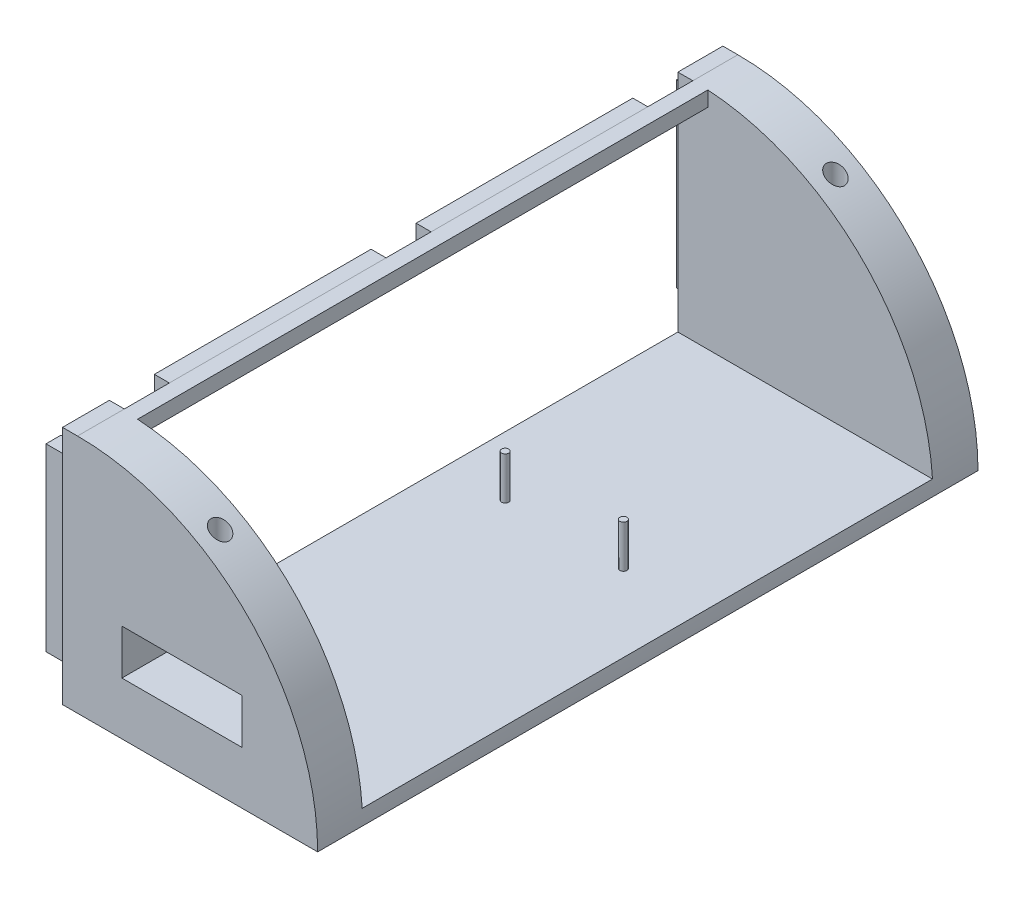
SolidWorks part; units mm, degrees
ref_plane "Front Plane" through (0, 0, 0) normal (0, 0, 1) x (1, 0, 0)
ref_plane "Top Plane" through (0, 0, 0) normal (0, 1, 0) x (1, 0, 0)
ref_plane "Right Plane" through (0, 0, 0) normal (1, 0, 0) x (0, 0, -1)
sketch "Sketch1" plane through (0, 0, 0) normal (0, 0, 1) x (1, 0, 0)
  line L0 (0, 0) -> (0, 50.8)
  line L1 (0, 0) -> (50.8, 0)
  arc A0 (0, 50.8) -> (50.8, 0) centre (0, 0) cw
  dimension "D1" = 50.8
  dimension "D2" = 50.8
extrude "Boss-Extrude1" add sketch "Sketch1" along normal blind 139.7
shell "Shell1" thickness 3.175
sketch "Sketch3" plane through (0, 0, 139.7) normal (0, 0, 1) x (1, 0, 0)
  line L0 (0, 50.8) -> (0, 0)
  line L1 (0, 0) -> (50.8, 0)
  arc A0 (0, 50.8) -> (50.8, 0) centre (0, 0) cw
extrude "Boss-Extrude2" add sketch "Sketch3" against normal blind 9.525
sketch "Sketch4" plane through (0, 0, 0) normal (0, 0, -1) x (-1, 0, 0)
  line L0 (-50.8, 0) -> (0, 0)
  line L1 (0, 0) -> (0, 50.8)
  arc A0 (-50.8, 0) -> (0, 50.8) centre (0, 0) cw
extrude "Boss-Extrude3" add sketch "Sketch4" against normal blind 9.525
sketch "Sketch5" plane through (0, 0, 0) normal (-1, 0, 0) x (0, 0, 1)
  line L1 (9.525, 47.625) -> (130.175, 47.625)
  line L2 (9.525, 47.625) -> (9.525, 3.175)
  line L3 (9.525, 3.175) -> (130.175, 3.175)
  line L4 (130.175, 47.625) -> (130.175, 3.175)
  line L5 (0, 50.8) -> (139.7, 50.8)
  line L6 (0, 50.8) -> (0, 0)
  line L7 (0, 0) -> (139.7, 0)
  line L8 (139.7, 50.8) -> (139.7, 0)
extrude "Boss-Extrude4" add sketch "Sketch5" along normal blind 3.175
sketch "Sketch6" plane through (-3.175, 0, 0) normal (-1, 0, 0) x (0, 0, 1)
  line L0 (0, 50.8) -> (0, 0) construction
  line L1 (1.5875, 6.35) -> (4.7625, 6.35)
  line L2 (1.5875, 6.35) -> (1.5875, 44.45)
  line L3 (1.5875, 44.45) -> (4.7625, 44.45)
  line L4 (4.7625, 6.35) -> (4.7625, 44.45)
  line L5 (1.5875, 6.35) -> (4.7625, 44.45) construction
  line L6 (1.5875, 44.45) -> (4.7625, 6.35) construction
  line L7 (139.7, 50.8) -> (0, 50.8) construction
  line L8 (69.85, 47.625) -> (69.85, 3.175) construction
  line L9 (130.175, 47.625) -> (9.525, 47.625) construction
  line L10 (9.525, 3.175) -> (130.175, 3.175) construction
  line L11 (138.1125, 44.45) -> (134.9375, 44.45)
  line L12 (134.9375, 6.35) -> (134.9375, 44.45)
  line L13 (138.1125, 6.35) -> (134.9375, 6.35)
  line L14 (138.1125, 6.35) -> (138.1125, 44.45)
  point P0 (3.175, 25.4)
  dimension "D1" = 38.1
  dimension "D2" = 3.175
  dimension "D3" = 3.175
  dimension "D4" = 25.4
extrude "Boss-Extrude5" add sketch "Sketch6" along normal blind 5.08
sketch "Sketch7" plane through (0, 50.8, 0) normal (0, 1, 0) x (1, 0, 0)
  line L0 (0, -139.7) -> (0, 0) construction
  line L1 (-3.175, -9.525) -> (0, -9.525)
  line L2 (-3.175, -9.525) -> (-3.175, -19.05)
  line L3 (-3.175, -19.05) -> (0, -19.05)
  line L4 (0, -9.525) -> (0, -19.05)
  line L5 (-3.175, -64.897) -> (-3.175, -74.422)
  line L6 (-3.175, -64.897) -> (0, -64.897)
  line L7 (0, -64.897) -> (0, -74.422)
  line L8 (-3.175, -74.422) -> (0, -74.422)
  line L9 (-3.175, -120.269) -> (-3.175, -129.794)
  line L10 (-3.175, -120.269) -> (0, -120.269)
  line L11 (0, -120.269) -> (0, -129.794)
  line L12 (-3.175, -129.794) -> (0, -129.794)
  dimension "D1" = 9.525
  dimension "D2" = 3
extrude "Cut-Extrude1" cut sketch "Sketch7" against normal up to surface (3.175 mm away) up to face at (-1.5875, 47.625, 69.85)
sketch "Sketch9" plane through (0, 3.175, 0) normal (0, 1, 0) x (1, 0, 0)
  line L0 (50.8, -139.7) -> (50.8, 0) construction
  line L1 (3.175, -9.525) -> (50.8, -9.525)
  line L2 (3.175, -9.525) -> (3.175, -130.175)
  line L3 (3.175, -130.175) -> (50.8, -130.175)
  line L4 (50.8, -9.525) -> (50.8, -130.175)
  line L5 (50.8, 0) -> (0, 0) construction
  line L6 (0, -139.7) -> (50.8, -139.7) construction
  line L7 (-3.175, -120.269) -> (-3.175, -74.422) construction
  dimension "D1" = 9.525
  dimension "D2" = 9.525
  dimension "D3" = 6.35
extrude "Cut-Extrude2" cut sketch "Sketch9" along normal through all
sketch "Sketch8" plane through (0, 3.175, 0) normal (0, 1, 0) x (1, 0, 0)
  circle A0 centre (34.3737, -124.5927) radius 0.75
  circle A1 centre (34.3737, -58.5927) radius 0.75
  circle A2 centre (9.3737, -58.5927) radius 0.75
  circle A3 centre (9.3737, -124.5927) radius 0.75
  point P8 (0, 0)
  point P9 (0, 0)
  point P10 (0, 0)
  point P11 (0, 0)
  point P12 (0, 0)
  point P13 (34.3737, -58.5927)
  dimension "D3" = 1.5
  dimension "D1" = 66
  dimension "D2" = 25
extrude "Boss-Extrude6" add sketch "Sketch8" along normal blind 9
sketch "Sketch10" plane through (0, 0, 130.175) normal (0, 0, -1) x (-1, 0, 0)
  line L1 (-34.7883, 11.1462) -> (-9.3883, 11.1462)
  line L2 (-34.7883, 11.1462) -> (-34.7883, 20.6712)
  line L3 (-34.7883, 20.6712) -> (-9.3883, 20.6712)
  line L4 (-9.3883, 11.1462) -> (-9.3883, 20.6712)
  dimension "D1" = 25.4
  dimension "D2" = 9.525
extrude "Cut-Extrude3" cut sketch "Sketch10" against normal through all
sketch "Sketch11" plane through (0, 50.8, 0) normal (0, 1, 0) x (1, 0, 0)
  line L0 (0, -9.525) -> (0, 0) construction
  line L1 (50.8, 0) -> (0, 0) construction
  line L2 (3.175, -69.85) -> (50.7007, -69.85) construction
  line L3 (3.175, -9.525) -> (3.175, -130.175) construction
  line L4 (50.7007, -130.175) -> (50.7007, -9.525) construction
  circle A0 centre (25.4, -4.7625) radius 1.905
  circle A1 centre (25.4, -134.9375) radius 1.905
  dimension "D1" = 3.81
  dimension "D2" = 25.4
  dimension "D3" = 4.7625
extrude "Cut-Extrude4" cut sketch "Sketch11" against normal blind 25.4
